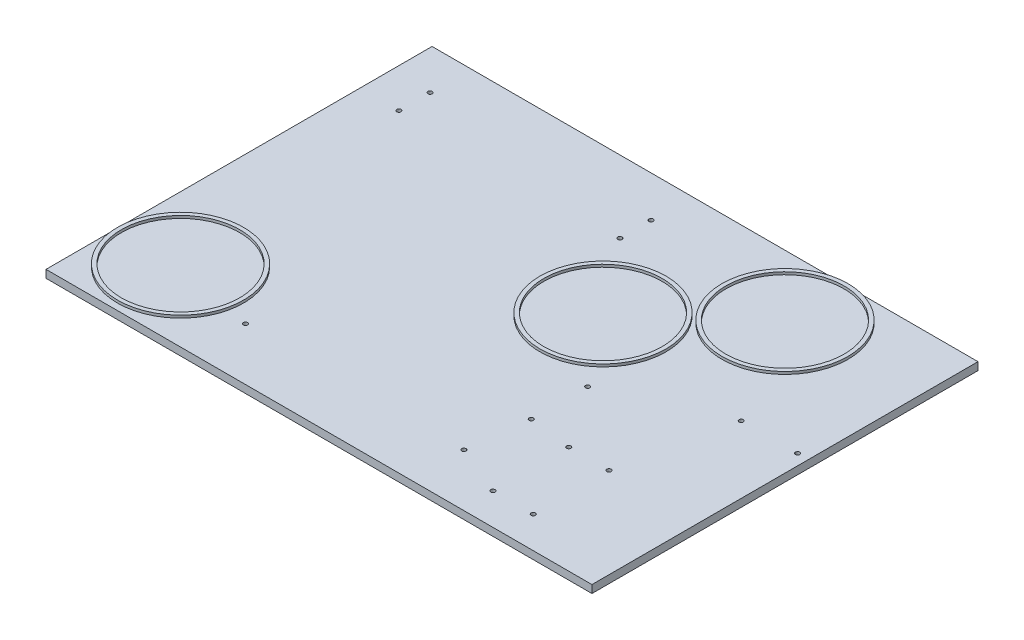
SolidWorks part; units mm, degrees
ref_plane "Front Plane" through (0, 0, 0) normal (0, 0, 1) x (1, 0, 0)
ref_plane "Top Plane" through (0, 0, 0) normal (0, 1, 0) x (1, 0, 0)
ref_plane "Right Plane" through (0, 0, 0) normal (1, 0, 0) x (0, 0, -1)
other "Configuration Table"
sketch "Sketch1" plane through (0, 0, 0) normal (0, 1, 0) x (1, 0, 0)
  line L1 (-210, -148.5) -> (210, -148.5)
  line L2 (-210, -148.5) -> (-210, 148.5)
  line L3 (-210, 148.5) -> (210, 148.5)
  line L4 (210, -148.5) -> (210, 148.5)
  line L5 (-210, -148.5) -> (210, 148.5) construction
  line L6 (-210, 148.5) -> (210, -148.5) construction
  point P6 (0, 0)
  dimension "D1" = 420
  dimension "D2" = 297
extrude "Plate" add sketch "Sketch1" along normal blind 6
sketch "Sketch2" plane through (0, 0, 0) normal (0, 1, 0) x (1, 0, 0)
  circle A0 centre (-97, -108) radius 1.65
  circle A1 centre (71, -108) radius 1.65
  circle A2 centre (-180, 117) radius 1.65
  circle A3 centre (-180, 93) radius 1.65
  circle A4 centre (-10, 117) radius 1.65
  circle A5 centre (-10, 93) radius 1.65
  circle A6 centre (109.5, -65.85) radius 1.65
  circle A7 centre (109.5, -124.15) radius 1.65
  circle A8 centre (140.5, -65.85) radius 1.65
  circle A9 centre (140.5, -124.15) radius 1.65
  circle A10 centre (158.3225, 18) radius 1.65
  circle A11 centre (201.6775, 18) radius 1.65
  circle A12 centre (76.5, -18.3225) radius 1.65
  circle A13 centre (76.5, -61.6775) radius 1.65
  dimension "D1" = 3.3
  dimension "D2" = 3.3
  dimension "D3" = 3.3
  dimension "D4" = 3.3
  dimension "D5" = 3.3
  dimension "D6" = 3.3
  dimension "D7" = 3.3
  dimension "D8" = 3.3
  dimension "D9" = 3.3
  dimension "D10" = 3.3
  dimension "D11" = 3.3
  dimension "D12" = 3.3
  dimension "D13" = 3.3
  dimension "D14" = 3.3
extrude "Tapped_Holes_M4" cut sketch "Sketch2" along normal through all and the other way through all
sketch "Sketch3" plane through (0, 0, 0) normal (0, 1, 0) x (1, 0, 0)
  circle A0 centre (-160, -95) radius 45.5
  circle A1 centre (-160, -95) radius 48.5
  circle A2 centre (35, 35) radius 45.5
  circle A3 centre (35, 35) radius 48.5
  circle A4 centre (110, 100) radius 45.5
  circle A5 centre (110, 100) radius 48.5
  dimension "D1" = 91
  dimension "D2" = 97
  dimension "D3" = 91
  dimension "D4" = 97
  dimension "D5" = 91
  dimension "D6" = 97
extrude "Jar_Locating_Rings" add sketch "Sketch3" along normal blind 2 from offset 6
equation "\"Jar_OD\"= 90  'ASSUMED - Part G fallback - jar outer diameter"
equation "\"Jar_H\"= 120  'ASSUMED - Part G fallback - jar height"
equation "\"Pump_L\"= 45  'ASSUMED - Part G fallback"
equation "\"Pump_W\"= 24  'ASSUMED - Part G fallback"
equation "\"Pump_H\"= 33  'ASSUMED - Part G fallback"
equation "\"Pump_Outlet_OD\"= 7.5  'ASSUMED - Part G fallback"
equation "\"Tube_OD\"= 8  'ASSUMED - Part G fallback"
equation "\"Tube_ID\"= 6  'ASSUMED - Part G fallback"
equation "\"TDS_Body_Dia\"= 12  'ASSUMED - Part G fallback"
equation "\"TDS_Wet_Len\"= 45  'ASSUMED - Part G fallback - length in water"
equation "\"DS_Tube_Dia\"= 6  'ASSUMED - Part G fallback"
equation "\"DS_Tube_Len\"= 50  'ASSUMED - Part G fallback"
equation "\"ORP_Body_Dia\"= 12  'ASSUMED - Part G fallback"
equation "\"ORP_Body_Len\"= 150  'ASSUMED - Part G fallback"
equation "\"ORP_Cap_Dia\"= 16  'ASSUMED - Part G fallback"
equation "\"Turb_W\"= 33  'ASSUMED - Part G fallback - head width"
equation "\"Turb_D\"= 28  'ASSUMED - Part G fallback - head depth"
equation "\"Turb_H\"= 30  'ASSUMED - Part G fallback - head height"
equation "\"Turb_Slot_W\"= 10  'ASSUMED - Part G fallback - slot width"
equation "\"Flow_L\"= 62  'ASSUMED - Part G fallback YF-S201"
equation "\"Flow_W\"= 36  'ASSUMED - Part G fallback"
equation "\"Flow_H\"= 35  'ASSUMED - Part G fallback"
equation "\"Thread_G12_OD\"= 20.955  'ASSUMED - Part G fallback thread G1/2 (major diameter)"
equation "\"Valve_L\"= 75  'ASSUMED - Part G fallback"
equation "\"Valve_W\"= 45  'ASSUMED - Part G fallback"
equation "\"Valve_H\"= 60  'ASSUMED - Part G fallback"
equation "\"Tee_L\"= 40  'ASSUMED - Part G fallback - overall length"
equation "\"Tee_Branch_L\"= 25  'ASSUMED - Part G fallback"
equation "\"Tee_OD\"= 12  'ASSUMED - Part G fallback"
equation "\"LED_Board_L\"= 20  'ASSUMED - Part G fallback"
equation "\"LED_Board_W\"= 20  'ASSUMED - Part G fallback - LED at centre"
equation "\"GUVA_L\"= 20  'ASSUMED - Part G fallback"
equation "\"GUVA_W\"= 12  'ASSUMED - Part G fallback - sensor at centre"
equation "\"Reed_L\"= 27  'ASSUMED - Part G fallback MC-38 half"
equation "\"Reed_W\"= 14  'ASSUMED - Part G fallback"
equation "\"Reed_H\"= 8  'ASSUMED - Part G fallback"
equation "\"ESP_L\"= 51  'ASSUMED - Part G fallback"
equation "\"ESP_W\"= 28  'ASSUMED - Part G fallback"
equation "\"TFT_L\"= 58  'ASSUMED - Part G fallback - board"
equation "\"TFT_W\"= 35  'ASSUMED - Part G fallback - board"
equation "\"TFT_Win_L\"= 35  'ASSUMED - Part G fallback - visible window"
equation "\"TFT_Win_W\"= 28  'ASSUMED - Part G fallback - visible window"
equation "\"Relay_L\"= 50  'ASSUMED - Part G fallback"
equation "\"Relay_W\"= 26  'ASSUMED - Part G fallback"
equation "\"Relay_H\"= 19  'ASSUMED - Part G fallback"
equation "\"Mosfet_L\"= 34  'ASSUMED - Part G fallback"
equation "\"Mosfet_W\"= 17  'ASSUMED - Part G fallback"
equation "\"Mosfet_H\"= 12  'ASSUMED - Part G fallback"
equation "\"TDS_Board_L\"= 42  'ASSUMED - Part G fallback"
equation "\"TDS_Board_W\"= 32  'ASSUMED - Part G fallback"
equation "\"Turb_Board_L\"= 38  'ASSUMED - Part G fallback"
equation "\"Turb_Board_W\"= 28  'ASSUMED - Part G fallback"
equation "\"BNC_Thread_Dia\"= 9.5  'ASSUMED - Part G fallback"
equation "\"Plate_L\"= 420  'ASSUMED - Part G fallback"
equation "\"Plate_W\"= 297  'ASSUMED - Part G fallback"
equation "\"Plate_T\"= 6  'ASSUMED - Part G fallback"
equation "\"Booster_L\"= 150  'ASSUMED - Part G fallback - booster pump"
equation "\"Booster_W\"= 95  'ASSUMED - Part G fallback"
equation "\"Booster_H\"= 100  'ASSUMED - Part G fallback"
equation "\"PTube_OD\"= 6.35  'ASSUMED - Part G fallback - product tube 1/4 inch"
equation "\"Qz_Out\"= 12  'ASSUMED - Part G fallback - quartz channel outside square"
equation "\"Qz_Path\"= 10  'ASSUMED - Part G fallback - quartz channel inside light path"
equation "\"Qz_L\"= 40  'ASSUMED - Part G fallback - quartz channel length"
equation "\"LED860_Dia\"= 5  'ASSUMED - Part G fallback - 860 nm LED"
equation "\"BPW_L\"= 5.4  'ASSUMED - Part G fallback - BPW34"
equation "\"BPW_W\"= 4.3  'ASSUMED - Part G fallback - BPW34"
equation "\"Cart_Dia\"= 50  'ASSUMED - Part G fallback - sediment and pre-carbon cartridges"
equation "\"Cart_L\"= 255  'ASSUMED - Part G fallback"
equation "\"UF_Dia\"= 50  'ASSUMED - Part G fallback - UF cartridge"
equation "\"UF_L\"= 260  'ASSUMED - Part G fallback"
equation "\"RO_Dia\"= 62  'ASSUMED - Part G fallback - RO membrane housing"
equation "\"RO_L\"= 300  'ASSUMED - Part G fallback"
equation "\"UVC_Dia\"= 40  'ASSUMED - Part G fallback - UV-C chamber"
equation "\"UVC_L\"= 300  'ASSUMED - Part G fallback"
equation "\"Tank_W\"= 260  'ASSUMED - Part G fallback - storage tank"
equation "\"Tank_D\"= 160  'ASSUMED - Part G fallback"
equation "\"Tank_H\"= 300  'ASSUMED - Part G fallback"
equation "\"Cab_W\"= 400  'ASSUMED - Part G fallback - purifier cabinet"
equation "\"Cab_D\"= 270  'ASSUMED - Part G fallback"
equation "\"Cab_H\"= 560  'ASSUMED - Part G fallback"
equation "\"ORP_Board_L\"= 40  'ASSUMED - Part G fallback - ORP buffer board"
equation "\"ORP_Board_W\"= 30  'ASSUMED - Part G fallback"
equation "\"Opt_Board_L\"= 50  'ASSUMED - Part G fallback - optical front-end board"
equation "\"Opt_Board_W\"= 40  'ASSUMED - Part G fallback"
equation "\"Buck_L\"= 43  'ASSUMED - Part G fallback - 12 V to 5 V buck module"
equation "\"Buck_W\"= 21  'ASSUMED - Part G fallback"
equation "\"Buck_H\"= 14  'ASSUMED - Part G fallback"
equation "\"BB_L\"= 165  'ASSUMED - Part G fallback - breadboard (As_Built_R3 only)"
equation "\"BB_W\"= 55  'ASSUMED - Part G fallback"
equation "\"BB_H\"= 10  'ASSUMED - Part G fallback"
equation "\"Cuv_W\"= 12.5  'ASSUMED - old R3 cuvette (station suppressed in SS4)"
equation "\"Cuv_D\"= 12.5  'ASSUMED - old R3 cuvette (station suppressed in SS4)"
equation "\"Cuv_H\"= 45  'ASSUMED - old R3 cuvette (station suppressed in SS4)"
equation "\"Probe_Clr\"= 0.3  'DESIGN VALUE - Part C rule 3 - printed probe hole = diameter + 0.3"
equation "\"Label_H\"= 0.6  'DESIGN VALUE - Part D - raised label height"
equation "\"D1@Sketch1\" = \"Plate_L\""
equation "\"D2@Sketch1\" = \"Plate_W\""
equation "\"D1@Plate\" = \"Plate_T\""
